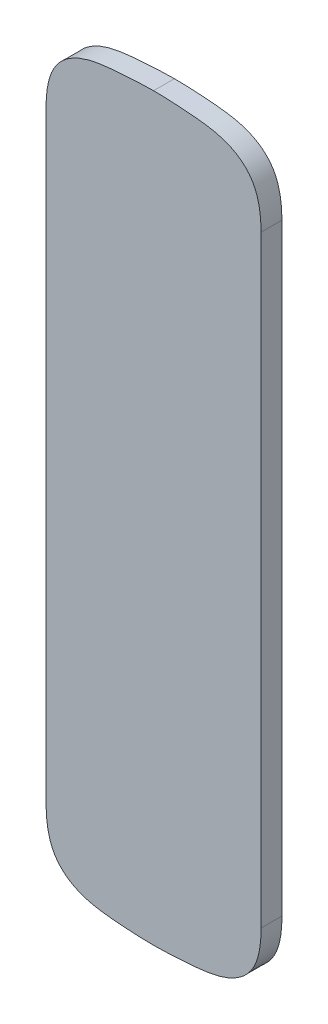
SolidWorks part; units mm, degrees
ref_plane "Front" through (0, 0, 0) normal (0, 0, 1) x (1, 0, 0)
ref_plane "Top" through (0, 0, 0) normal (0, 1, 0) x (1, 0, 0)
ref_plane "Right" through (0, 0, 0) normal (1, 0, 0) x (0, 0, -1)
sketch "草图1" plane through (0, 0, 0) normal (0, 0, 1) x (1, 0, 0)
  line L0 (-5.1565, -23.3957) -> (-5.1565, -52.2963)
  line L1 (5.1565, -52.2963) -> (5.1565, -23.3957)
  line L6 (-5.2565, -23.3957) -> (-5.2565, -52.2963) construction
  line L7 (5.2565, -52.2963) -> (5.2565, -23.3957) construction
  spline S0 degree 1 poles (-5.1565, -52.2963) (0, -55.5929) knots 0 0 1 1 construction
  spline S1 degree 1 poles (0, -55.5929) (5.1565, -52.2963) knots 0 0 1 1 construction
  spline S2 degree 1 poles (5.1565, -23.3957) (0, -20.0991) knots 0 0 1 1 construction
  spline S3 degree 1 poles (0, -20.0991) (-5.1565, -23.3957) knots 0 0 1 1 construction
  spline S4 degree 3 poles (-5.1565, -52.2963) (-5.1565, -52.592) (-5.1219, -53.1812) (-4.8836, -54.0635) (-4.3456, -54.7539) (-3.3099, -55.3532) (-2.0962, -55.49) (-1.0545, -55.5596) (-0.4778, -55.5873) (-0.1565, -55.5929) (0, -55.5929) knots 0 0 0 0 0.125 0.25 0.375001 0.500001 0.750001 0.875001 0.937501 1.000001 1.000001 1.000001 1.000001
  spline S5 degree 3 poles (0, -55.5929) (0.1565, -55.5929) (0.4778, -55.5873) (1.0545, -55.5596) (2.0962, -55.49) (3.3099, -55.3532) (4.3456, -54.7539) (4.8836, -54.0635) (5.1219, -53.1812) (5.1565, -52.592) (5.1565, -52.2963) knots -0.000001 -0.000001 -0.000001 -0.000001 0.062499 0.124999 0.249999 0.499999 0.624999 0.75 0.875 1 1 1 1
  spline S6 degree 3 poles (5.1565, -23.3957) (5.1565, -23.1) (5.1219, -22.5108) (4.8836, -21.6285) (4.3456, -20.9381) (3.3099, -20.3388) (2.0962, -20.202) (1.0545, -20.1324) (0.4778, -20.1047) (0.1565, -20.0991) (0, -20.0991) knots 0 0 0 0 0.125 0.25 0.375001 0.500001 0.750001 0.875001 0.937501 1.000001 1.000001 1.000001 1.000001
  spline S7 degree 3 poles (0, -20.0991) (-0.1565, -20.0991) (-0.4778, -20.1047) (-1.0545, -20.1324) (-2.0962, -20.202) (-3.3099, -20.3388) (-4.3456, -20.9381) (-4.8836, -21.6285) (-5.1219, -22.5108) (-5.1565, -23.1) (-5.1565, -23.3957) knots -0.000001 -0.000001 -0.000001 -0.000001 0.062499 0.124999 0.249999 0.499999 0.624999 0.75 0.875 1 1 1 1
  spline S8 degree 3 poles (5.2565, -23.3957) (5.2565, -22.7017) (5.1247, -21.6119) (4.17, -20.6883) (3.387, -20.3188) (2.3714, -20.1247) (1.2316, -20.0417) (0.4453, -19.9991) (0, -19.9991) knots 0 0 0 0 0.30116 0.404454 0.537204 0.652207 0.831341 1 1 1 1 construction
  spline S9 degree 3 poles (0, -19.9991) (-0.4453, -19.9991) (-1.2316, -20.0417) (-2.3714, -20.1247) (-3.387, -20.3188) (-4.17, -20.6883) (-5.1247, -21.6119) (-5.2565, -22.7017) (-5.2565, -23.3957) knots 0 0 0 0 0.168659 0.347793 0.462796 0.595546 0.69884 1 1 1 1 construction
  spline S10 degree 3 poles (-5.2565, -52.2963) (-5.2565, -52.9903) (-5.1247, -54.0801) (-4.17, -55.0037) (-3.387, -55.3732) (-2.3714, -55.5673) (-1.2316, -55.6503) (-0.4453, -55.6929) (0, -55.6929) knots 0 0 0 0 0.30116 0.404454 0.537204 0.652207 0.831341 1 1 1 1 construction
  spline S11 degree 3 poles (0, -55.6929) (0.4453, -55.6929) (1.2316, -55.6503) (2.3714, -55.5673) (3.387, -55.3732) (4.17, -55.0037) (5.1247, -54.0801) (5.2565, -52.9903) (5.2565, -52.2963) knots 0 0 0 0 0.168659 0.347793 0.462796 0.595546 0.69884 1 1 1 1 construction
  dimension "D1" = 0.1
extrude "凸台-拉伸1" add sketch "草图1" along normal blind 1
sketch "草图5"
sketch "草图3" [suppressed] plane through (0, 0, 1) normal (0, 0, 1) x (1, 0, 0)
  line L1 (-2.2247, -52.5921) -> (0.7217, -52.5921)
  line L2 (-2.2247, -52.5921) -> (-2.2247, -51.126)
  line L3 (-2.2247, -51.126) -> (0.7217, -51.126)
  line L4 (0.7217, -52.5921) -> (0.7217, -51.126)
  line L5 (-2.2247, -52.5921) -> (0.7217, -51.126) construction
  line L6 (-2.2247, -51.126) -> (0.7217, -52.5921) construction
  point P0 (-0.7515, -51.859)
ref_plane "基准面1" through (0, 0, 1.01) normal (0, 0, 1) x (1, 0, 0)
sketch "草图4" plane through (0, 0, 0.51) normal (0, 0, 1) x (1, 0, 0)
  line L0 (-37.9719, -42.3448) -> (303.3614, -42.3448) construction
  line L1 (0, -24.0288) -> (0, -24.0288) construction
